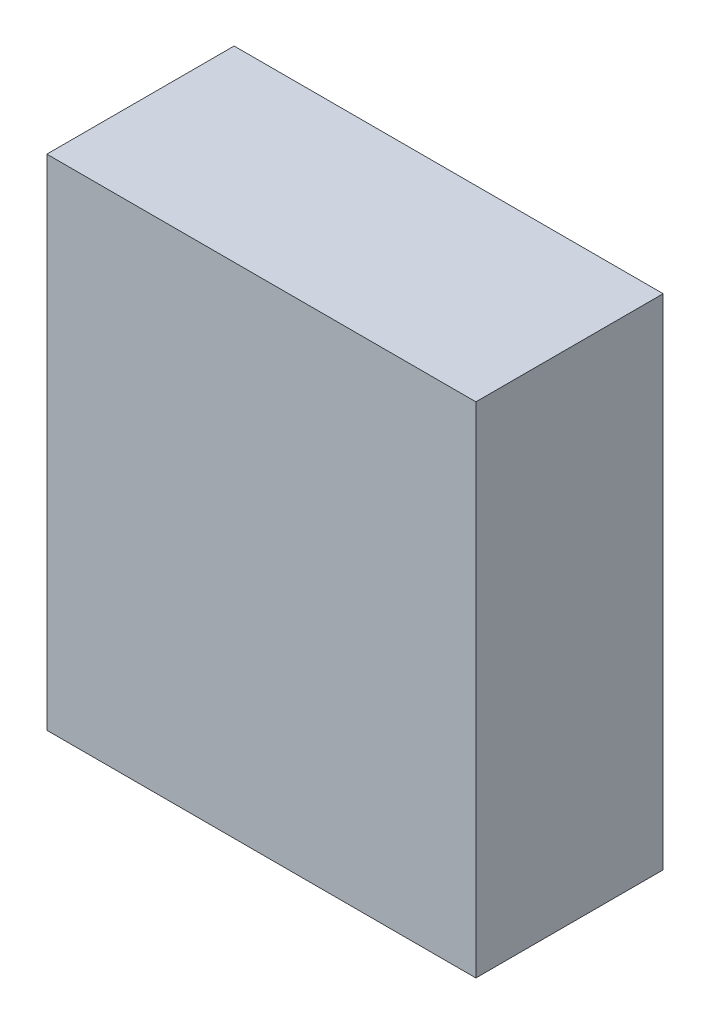
SolidWorks part; units mm, degrees
ref_plane "前视基准面" through (0, 0, 0) normal (0, 0, 1) x (1, 0, 0)
ref_plane "上视基准面" through (0, 0, 0) normal (0, 1, 0) x (1, 0, 0)
ref_plane "右视基准面" through (0, 0, 0) normal (1, 0, 0) x (0, 0, -1)
sketch "Sketch1" plane through (0, 0, 0) normal (0, 0, 1) x (1, 0, 0)
  line L1 (-43.1737, -13.3225) -> (-20.2639, -13.3225)
  line L2 (-43.1737, -13.3225) -> (-43.1737, 13.3225)
  line L3 (-43.1737, 13.3225) -> (-20.2639, 13.3225)
  line L4 (-20.2639, -13.3225) -> (-20.2639, 13.3225)
  line L5 (-43.1737, -13.3225) -> (-20.2639, 13.3225) construction
  line L6 (-43.1737, 13.3225) -> (-20.2639, -13.3225) construction
  point P0 (-31.7188, 0)
extrude "Boss-Extrude1" add sketch "Sketch1" along normal blind 10
